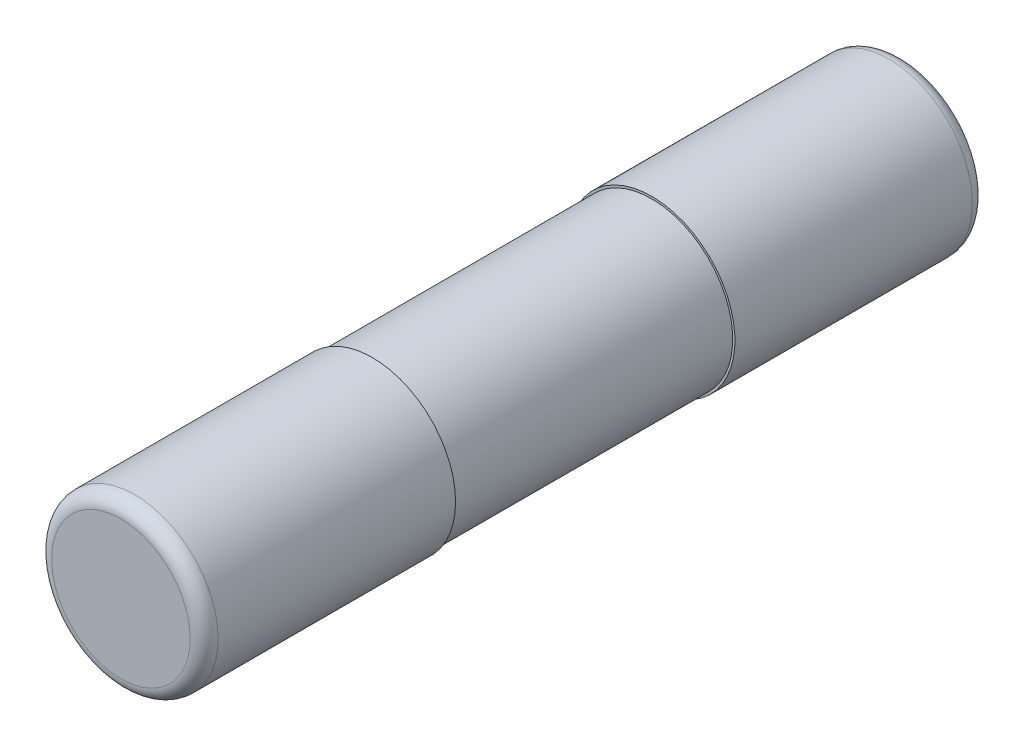
SolidWorks part; units mm, degrees
ref_plane "정면" through (0, 0, 0) normal (0, 0, 1) x (1, 0, 0)
ref_plane "윗면" through (0, 0, 0) normal (0, 1, 0) x (1, 0, 0)
ref_plane "우측면" through (0, 0, 0) normal (1, 0, 0) x (0, 0, -1)
sketch "스케치1" plane through (0, 0, 0) normal (0, 0, 1) x (1, 0, 0)
  circle A0 centre (0, 0) radius 1.45
  dimension "D1" = 2.9
extrude "보스-돌출1" add sketch "스케치1" along normal blind 5
sketch "스케치2" plane through (0, 0, 5) normal (0, 0, 1) x (1, 0, 0)
  circle A0 centre (0, 0) radius 1.49
  dimension "D1" = 2.98
extrude "보스-돌출2" add sketch "스케치2" along normal blind 4.5
sketch "스케치5" plane through (0, 0, 0) normal (0, 0, -1) x (-1, 0, 0)
  circle A0 centre (0, 0) radius 1.49
  dimension "D1" = 2.98
extrude "보스-돌출3" add sketch "스케치5" along normal blind 4.5
fillet "필렛1" radius 0.25 2 edges at (1.49, 0, 9.5) (-1.49, 0, -4.5)
